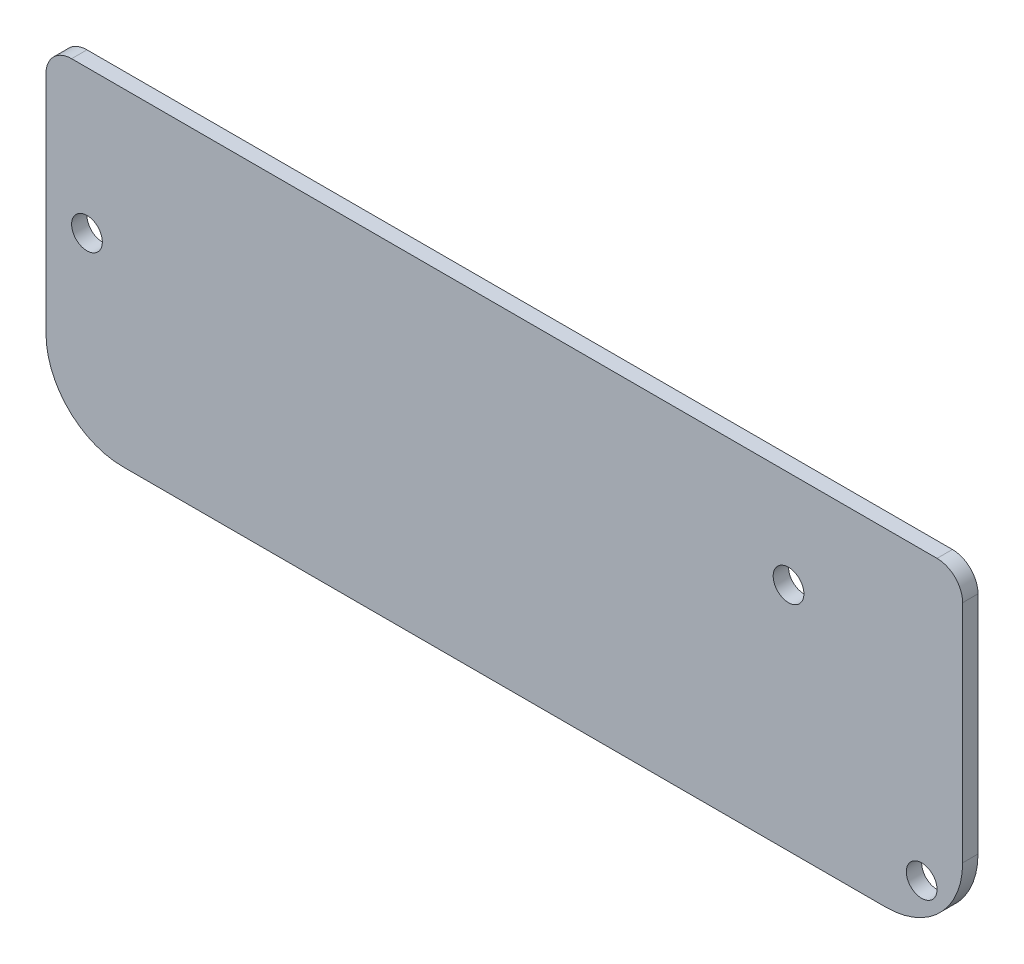
SolidWorks part; units mm, degrees
ref_plane "Plan de face" through (0, 0, 0) normal (0, 0, 1) x (1, 0, 0)
ref_plane "Plan de dessus" through (0, 0, 0) normal (0, 1, 0) x (1, 0, 0)
ref_plane "Plan de droite" through (0, 0, 0) normal (1, 0, 0) x (0, 0, -1)
sketch "Esquisse1" plane through (0, 0, 0) normal (0, 0, 1) x (1, 0, 0)
  line L1 (118.1017, 78.6323) -> (267.1017, 78.6323)
  line L2 (103.1017, 93.6323) -> (103.1017, 137.6323)
  line L3 (108.1017, 142.6323) -> (277.1017, 142.6323)
  line L4 (282.1017, 93.6323) -> (282.1017, 137.6323)
  arc A0 (277.1017, 142.6323) -> (282.1017, 137.6323) centre (277.1017, 137.6323) cw
  arc A1 (103.1017, 137.6323) -> (108.1017, 142.6323) centre (108.1017, 137.6323) cw
  arc A2 (267.1017, 78.6323) -> (282.1017, 93.6323) centre (267.1017, 93.6323) ccw
  arc A3 (118.1017, 78.6323) -> (103.1017, 93.6323) centre (118.1017, 93.6323) cw
  point P6 (282.1017, 142.6323)
  point P9 (103.1017, 142.6323)
  point P12 (282.1017, 78.6323)
  dimension "D3" = 5
  dimension "D4" = 15
  dimension "D1" = 179
  dimension "D2" = 64
extrude "Boss.-Extru.1" add sketch "Esquisse1" along normal blind 3
sketch "Esquisse2" plane through (0, 0, 0) normal (0, 0, -1) x (-1, 0, 0)
  line L0 (-103.1017, 137.6323) -> (-103.1017, 93.6323) construction
  line L1 (-118.1017, 78.6323) -> (-267.1017, 78.6323) construction
  line L2 (-282.1017, 93.6323) -> (-282.1017, 137.6323) construction
  line L3 (-277.1017, 142.6323) -> (-108.1017, 142.6323) construction
  circle A0 centre (-111.1017, 114.6323) radius 3
  circle A1 centre (-111.1017, 86.6323) radius 3
  circle A2 centre (-248.1017, 123.6323) radius 3
  circle A3 centre (-274.1017, 86.6323) radius 3
  point P14 (-277.4029, 79.7448)
  dimension "D1" = 8
  dimension "D2" = 8
  dimension "D3" = 8
  dimension "D4" = 8
  dimension "D5" = 19
  dimension "D6" = 34
  dimension "D7" = 8
  dimension "D8" = 28
extrude "Enlèv. mat.-Extru.1" cut sketch "Esquisse2" against normal blind 3 contours A0 | A2 | A3
